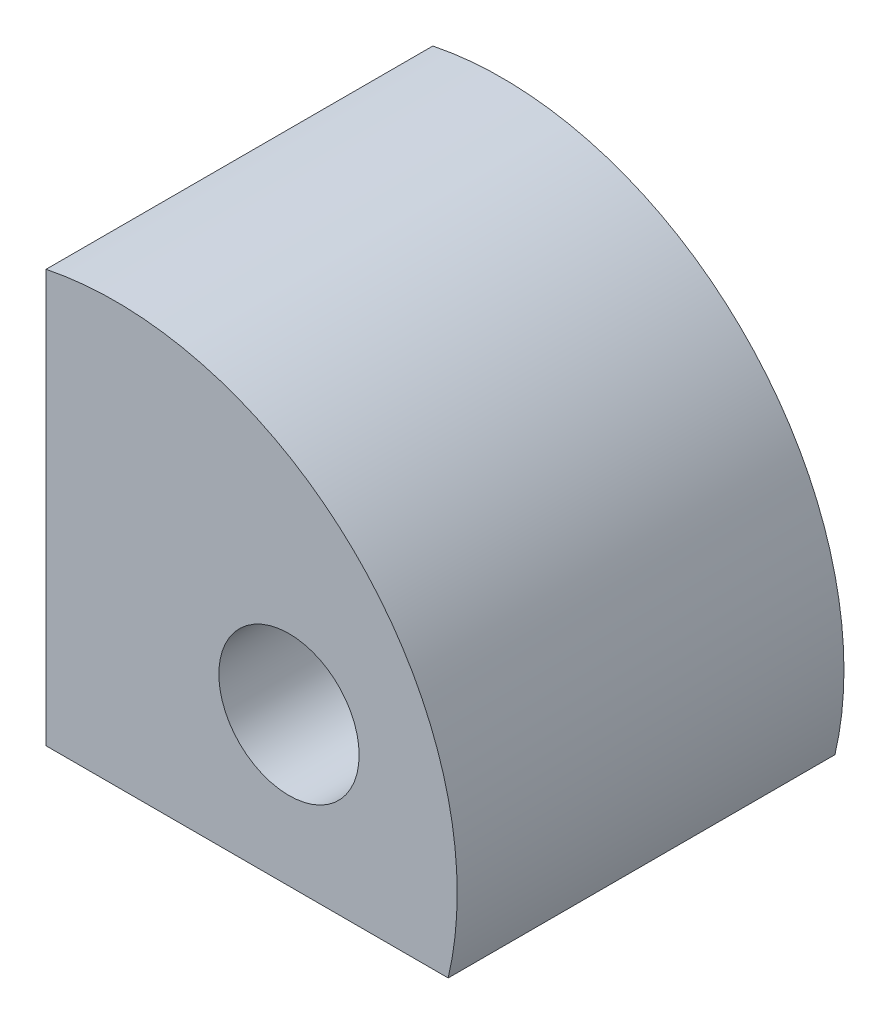
SolidWorks part; units mm, degrees
ref_plane "Front Plane" through (0, 0, 0) normal (0, 0, 1) x (1, 0, 0)
ref_plane "Top Plane" through (0, 0, 0) normal (0, 1, 0) x (1, 0, 0)
ref_plane "Right Plane" through (0, 0, 0) normal (1, 0, 0) x (0, 0, -1)
sketch "Sketch1" plane through (0, 0, 0) normal (0, 0, 1) x (1, 0, 0)
  line L22 (6.8525, -4.749) -> (-2.8942, -4.749)
  line L23 (-2.8942, 5.2522) -> (-2.8942, -4.749)
  circle A8 centre (2.9937, -1.149) radius 1.7
  arc A11 (6.8525, -4.749) -> (-2.8942, 5.2522) centre (-1.2151, -2.8614) ccw
  dimension "D3" = 3.4
  dimension "D1" = 3.6
extrude "Boss-Extrude1" add sketch "Sketch1" along normal blind 9.3733
